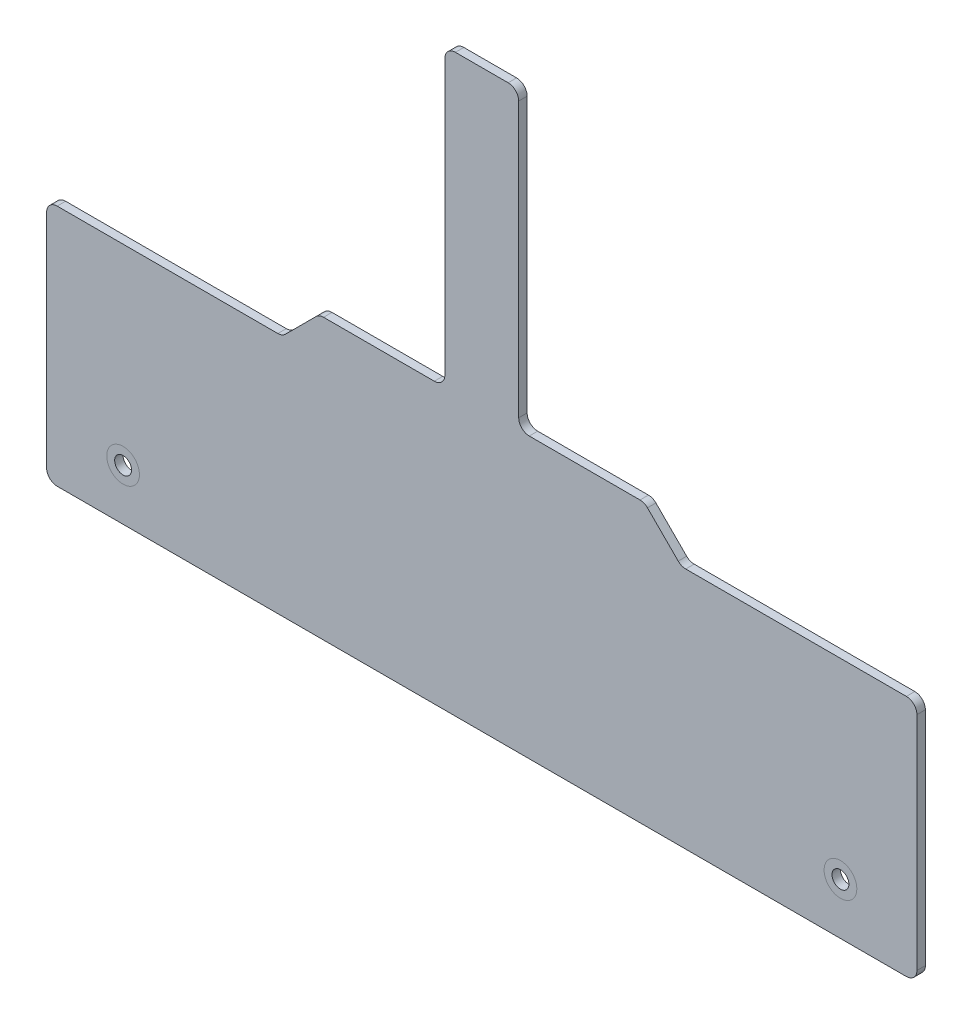
SolidWorks part; units mm, degrees
ref_plane "Front" through (0, 0, 0) normal (0, 0, 1) x (1, 0, 0)
ref_plane "Top" through (0, 0, 0) normal (0, 1, 0) x (1, 0, 0)
ref_plane "Right" through (0, 0, 0) normal (1, 0, 0) x (0, 0, -1)
sketch "Sketch2" plane through (0, 7465.171, 0) normal (0, 0, -1) x (1, 0, 0)
  line L0 (0, 14930.342) -> (0, -35069.658) construction
  line L1 (285.758, 7465.171) -> (-49714.242, 7465.171) construction
  line L2 (-4.5, 7427.1895) -> (4.5, 7427.1895)
  line L3 (4.5, 7427.1895) -> (4.5, 7421.8895)
  line L4 (4.5, 7421.8895) -> (-4.5, 7421.8895)
  line L5 (-4.5, 7421.8895) -> (-4.5, 7427.1895)
  line L6 (-4.5, 7420.8495) -> (4.5, 7420.8495)
  line L7 (4.5, 7420.8495) -> (4.5, 7415.5495)
  line L8 (4.5, 7415.5495) -> (-4.5, 7415.5495)
  line L9 (-4.5, 7415.5495) -> (-4.5, 7420.8495)
  line L10 (37.2426, 7456.5852) -> (31.4142, 7450.7568)
  line L12 (80.5, 7457.171) -> (38.6569, 7457.171)
  line L13 (82.5, 7501.171) -> (82.5, 7459.171)
  line L17 (0, 7415.171) -> (0, 7515.171) construction
  line L18 (-4.5, 7414.5095) -> (4.5, 7414.5095)
  line L19 (4.5, 7414.5095) -> (4.5, 7409.2095)
  line L20 (4.5, 7409.2095) -> (-4.5, 7409.2095)
  line L21 (-4.5, 7409.2095) -> (-4.5, 7414.5095)
  line L22 (-4.5, 7408.1695) -> (4.5, 7408.1695)
  line L23 (4.5, 7408.1695) -> (4.5, 7402.8695)
  line L24 (4.5, 7402.8695) -> (-4.5, 7402.8695)
  line L25 (-4.5, 7402.8695) -> (-4.5, 7408.1695)
  line L26 (-4.5, 7433.5295) -> (-4.5, 7427.1895) construction
  line L27 (-4.5, 7401.8295) -> (4.5, 7401.8295)
  line L28 (4.5, 7401.8295) -> (4.5, 7396.5295)
  line L29 (4.5, 7396.5295) -> (-4.5, 7396.5295)
  line L30 (-4.5, 7396.5295) -> (-4.5, 7401.8295)
  line L31 (-50, 7465.171) -> (50, 7465.171) construction
  line L64 (-80.5, 7457.171) -> (-38.6569, 7457.171)
  line L65 (-37.2426, 7456.5852) -> (-31.4142, 7450.7568)
  line L66 (-30, 7450.171) -> (-9, 7450.171)
  line L67 (-7, 7448.171) -> (-7, 7396.171)
  line L68 (-5, 7394.171) -> (5, 7394.171)
  line L69 (7, 7396.171) -> (7, 7448.171)
  line L70 (9, 7450.171) -> (30, 7450.171)
  line L80 (80.5, 7503.171) -> (-80.5, 7503.171)
  line L87 (-82.5, 7501.171) -> (-82.5, 7459.171)
  line L108 (-4.5, 7433.5295) -> (4.5, 7433.5295)
  line L109 (4.5, 7433.5295) -> (4.5, 7428.2295)
  line L110 (4.5, 7428.2295) -> (-4.5, 7428.2295)
  line L111 (-4.5, 7428.2295) -> (-4.5, 7433.5295)
  arc A0 (30, 7450.171) -> (31.4142, 7450.7568) centre (30, 7452.171) ccw
  arc A1 (-82.5, 7459.171) -> (-80.5, 7457.171) centre (-80.5, 7459.171) ccw
  circle A2 centre (-68, 7493.4706) radius 1.6
  arc A3 (38.6569, 7457.171) -> (37.2426, 7456.5852) centre (38.6569, 7455.171) ccw
  circle A4 centre (68, 7493.4706) radius 1.6
  arc A5 (-38.6569, 7457.171) -> (-37.2426, 7456.5852) centre (-38.6569, 7455.171) cw
  circle A6 centre (68, 7493.4706) radius 3.1
  circle A7 centre (-68, 7493.4706) radius 3.1
  arc A8 (-30, 7450.171) -> (-31.4142, 7450.7568) centre (-30, 7452.171) cw
  arc A9 (-9, 7450.171) -> (-7, 7448.171) centre (-9, 7448.171) cw
  arc A10 (-80.5, 7503.171) -> (-82.5, 7501.171) centre (-80.5, 7501.171) ccw
  arc A11 (9, 7450.171) -> (7, 7448.171) centre (9, 7448.171) ccw
  arc A12 (80.5, 7503.171) -> (82.5, 7501.171) centre (80.5, 7501.171) cw
  arc A13 (82.5, 7459.171) -> (80.5, 7457.171) centre (80.5, 7459.171) cw
  arc A47 (-7, 7396.171) -> (-5, 7394.171) centre (-5, 7396.171) ccw
  arc A48 (5, 7394.171) -> (7, 7396.171) centre (5, 7396.171) ccw
  dimension "D1" = 3.2
  dimension "D2" = 1.5
  dimension "D7" = 38
  dimension "D8" = 2
  dimension "D9" = 165
  dimension "D10" = 9
  dimension "D11" = 5.3
  dimension "D12" = 2
  dimension "D13" = 31.6415
  dimension "D16" = 45
  dimension "D20" = 2
  dimension "D3" = 28.2996
  dimension "D4" = 136
  dimension "D5" = 15
  dimension "D6" = 60
  dimension "D14" = 14
  dimension "D15" = 71
  dimension "D17" = 8
  dimension "D18" = 6
  dimension "D19" = 6.34
extrude "Boss-Extrude1" add sketch "Sketch2" along normal blind 1.6 separate body contours A48 L68 A47 L67 A9 L66 A8 L65 A5 L64 A1 L87 A10 L80 A12 L13 A13 L12 A3 L10 A0 L70 A11 L69 A6 L111 L110 L109 L108 L30 L29 L28 L27 L25 L24 L23 L22 L21 L20 L19 L18 L9 L8 L7 L6 | A7 A2 | A6 A4 | L110 L111 L108 L109 | L4 L5 L2 L3 | L8 L9 L6 L7 | L20 L21 L18 L19 | L24 L25 L22 L23 | L29 L30 L27 L28
sketch "Sketch3" plane through (0, 0, 0) normal (0, 0, 1) x (1, 0, 0)
  circle A0 centre (-68, -28.2996) radius 3.1 construction
  circle A1 centre (68, -28.2996) radius 3.1 construction
  circle A2 centre (-68, -28.2996) radius 3.1
  circle A3 centre (68, -28.2996) radius 3.1
split line "Split Line1"
sketch "Sketch4" plane through (0, 0, -1.6) normal (0, 0, -1) x (-1, 0, 0)
  line L0 (-4.5, 63.3415) -> (-4.5, 68.6415) construction
  line L1 (-4.5, 68.6415) -> (4.5, 68.6415) construction
  line L2 (4.5, 68.6415) -> (4.5, 63.3415) construction
  line L3 (4.5, 63.3415) -> (-4.5, 63.3415) construction
  line L4 (-4.5, 57.0015) -> (-4.5, 62.3015) construction
  line L5 (-4.5, 62.3015) -> (4.5, 62.3015) construction
  line L6 (4.5, 62.3015) -> (4.5, 57.0015) construction
  line L7 (4.5, 57.0015) -> (-4.5, 57.0015) construction
  line L8 (-4.5, 50.6615) -> (-4.5, 55.9615) construction
  line L9 (-4.5, 55.9615) -> (4.5, 55.9615) construction
  line L10 (4.5, 55.9615) -> (4.5, 50.6615) construction
  line L11 (4.5, 50.6615) -> (-4.5, 50.6615) construction
  line L12 (-4.5, 44.3215) -> (-4.5, 49.6215) construction
  line L13 (-4.5, 49.6215) -> (4.5, 49.6215) construction
  line L14 (4.5, 49.6215) -> (4.5, 44.3215) construction
  line L15 (4.5, 44.3215) -> (-4.5, 44.3215) construction
  line L16 (-4.5, 37.9815) -> (-4.5, 43.2815) construction
  line L17 (-4.5, 43.2815) -> (4.5, 43.2815) construction
  line L18 (4.5, 43.2815) -> (4.5, 37.9815) construction
  line L19 (4.5, 37.9815) -> (-4.5, 37.9815) construction
  line L20 (-4.5, 31.6415) -> (-4.5, 36.9415) construction
  line L21 (-4.5, 36.9415) -> (4.5, 36.9415) construction
  line L22 (4.5, 36.9415) -> (4.5, 31.6415) construction
  line L23 (4.5, 31.6415) -> (-4.5, 31.6415) construction
  line L24 (-4.5, 63.3415) -> (-4.5, 68.6415)
  line L25 (-4.5, 68.6415) -> (4.5, 68.6415)
  line L26 (4.5, 68.6415) -> (4.5, 63.3415)
  line L27 (4.5, 63.3415) -> (-4.5, 63.3415)
  line L28 (-4.5, 57.0015) -> (-4.5, 62.3015)
  line L29 (-4.5, 62.3015) -> (4.5, 62.3015)
  line L30 (4.5, 62.3015) -> (4.5, 57.0015)
  line L31 (4.5, 57.0015) -> (-4.5, 57.0015)
  line L32 (-4.5, 50.6615) -> (-4.5, 55.9615)
  line L33 (-4.5, 55.9615) -> (4.5, 55.9615)
  line L34 (4.5, 55.9615) -> (4.5, 50.6615)
  line L35 (4.5, 50.6615) -> (-4.5, 50.6615)
  line L36 (-4.5, 44.3215) -> (-4.5, 49.6215)
  line L37 (-4.5, 49.6215) -> (4.5, 49.6215)
  line L38 (4.5, 49.6215) -> (4.5, 44.3215)
  line L39 (4.5, 44.3215) -> (-4.5, 44.3215)
  line L40 (-4.5, 37.9815) -> (-4.5, 43.2815)
  line L41 (-4.5, 43.2815) -> (4.5, 43.2815)
  line L42 (4.5, 43.2815) -> (4.5, 37.9815)
  line L43 (4.5, 37.9815) -> (-4.5, 37.9815)
  line L44 (-4.5, 31.6415) -> (-4.5, 36.9415)
  line L45 (-4.5, 36.9415) -> (4.5, 36.9415)
  line L46 (4.5, 36.9415) -> (4.5, 31.6415)
  line L47 (4.5, 31.6415) -> (-4.5, 31.6415)
split line "Split Line2"
sketch "Sketch5" plane through (0, 0, -1.6) normal (0, 0, -1) x (-1, 0, 0)
  line L4 (-4.5, 68.6415) -> (-4.5, 63.3415)
  line L5 (-4.5, 63.3415) -> (4.5, 63.3415)
  line L6 (4.5, 63.3415) -> (4.5, 68.6415)
  line L7 (4.5, 68.6415) -> (-4.5, 68.6415)
  line L8 (-4.5, 68.6415) -> (-4.5, 63.3415)
  line L9 (-4.5, 63.3415) -> (4.5, 63.3415)
  line L10 (4.5, 63.3415) -> (4.5, 68.6415)
  line L11 (4.5, 68.6415) -> (-4.5, 68.6415)
  line L12 (-4.5, 62.3015) -> (-4.5, 57.0015)
  line L13 (-4.5, 57.0015) -> (4.5, 57.0015)
  line L14 (4.5, 57.0015) -> (4.5, 62.3015)
  line L15 (4.5, 62.3015) -> (-4.5, 62.3015)
  line L16 (-4.5, 62.3015) -> (-4.5, 57.0015)
  line L17 (-4.5, 57.0015) -> (4.5, 57.0015)
  line L18 (4.5, 57.0015) -> (4.5, 62.3015)
  line L19 (4.5, 62.3015) -> (-4.5, 62.3015)
  line L20 (-4.5, 55.9615) -> (-4.5, 50.6615)
  line L21 (-4.5, 50.6615) -> (4.5, 50.6615)
  line L22 (4.5, 50.6615) -> (4.5, 55.9615)
  line L23 (4.5, 55.9615) -> (-4.5, 55.9615)
  line L24 (-4.5, 55.9615) -> (-4.5, 50.6615)
  line L25 (-4.5, 50.6615) -> (4.5, 50.6615)
  line L26 (4.5, 50.6615) -> (4.5, 55.9615)
  line L27 (4.5, 55.9615) -> (-4.5, 55.9615)
  line L28 (-4.5, 49.6215) -> (-4.5, 44.3215)
  line L29 (-4.5, 44.3215) -> (4.5, 44.3215)
  line L30 (4.5, 44.3215) -> (4.5, 49.6215)
  line L31 (4.5, 49.6215) -> (-4.5, 49.6215)
  line L32 (-4.5, 49.6215) -> (-4.5, 44.3215)
  line L33 (-4.5, 44.3215) -> (4.5, 44.3215)
  line L34 (4.5, 44.3215) -> (4.5, 49.6215)
  line L35 (4.5, 49.6215) -> (-4.5, 49.6215)
  line L36 (-4.5, 43.2815) -> (-4.5, 37.9815)
  line L37 (-4.5, 37.9815) -> (4.5, 37.9815)
  line L38 (4.5, 37.9815) -> (4.5, 43.2815)
  line L39 (4.5, 43.2815) -> (-4.5, 43.2815)
  line L40 (-4.5, 43.2815) -> (-4.5, 37.9815)
  line L41 (-4.5, 37.9815) -> (4.5, 37.9815)
  line L42 (4.5, 37.9815) -> (4.5, 43.2815)
  line L43 (4.5, 43.2815) -> (-4.5, 43.2815)
  line L44 (-4.5, 36.9415) -> (-4.5, 31.6415)
  line L45 (-4.5, 31.6415) -> (4.5, 31.6415)
  line L46 (4.5, 31.6415) -> (4.5, 36.9415)
  line L47 (4.5, 36.9415) -> (-4.5, 36.9415)
  line L48 (-4.5, 36.9415) -> (-4.5, 31.6415)
  line L49 (-4.5, 31.6415) -> (4.5, 31.6415)
  line L50 (4.5, 31.6415) -> (4.5, 36.9415)
  line L51 (4.5, 36.9415) -> (-4.5, 36.9415)
  dimension "D1" = 0
  dimension "D2" = 0
  dimension "D3" = 0
  dimension "D4" = 0
  dimension "D5" = 0
  dimension "D6" = 0
